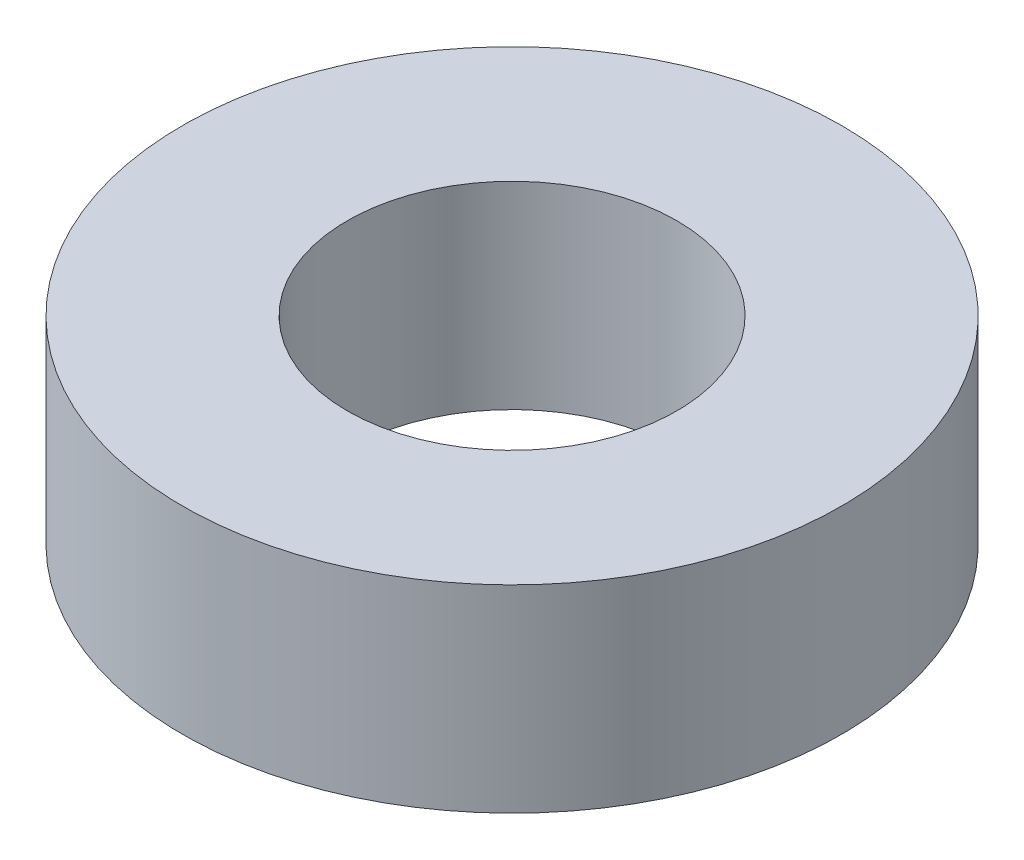
SolidWorks part; units mm, degrees
ref_plane "Front Plane" through (0, 0, 0) normal (0, 0, 1) x (1, 0, 0)
ref_plane "Top Plane" through (0, 0, 0) normal (0, 1, 0) x (1, 0, 0)
ref_plane "Right Plane" through (0, 0, 0) normal (1, 0, 0) x (0, 0, -1)
sketch "Sketch1" plane through (0, 0, 0) normal (0, 1, 0) x (1, 0, 0)
  circle A0 centre (0, 0) radius 1.5875
  circle A1 centre (0, 0) radius 3.175
  dimension "D1" = 3.175
  dimension "D2" = 6.35
extrude "Boss-Extrude1" add sketch "Sketch1" along normal blind 1.905
